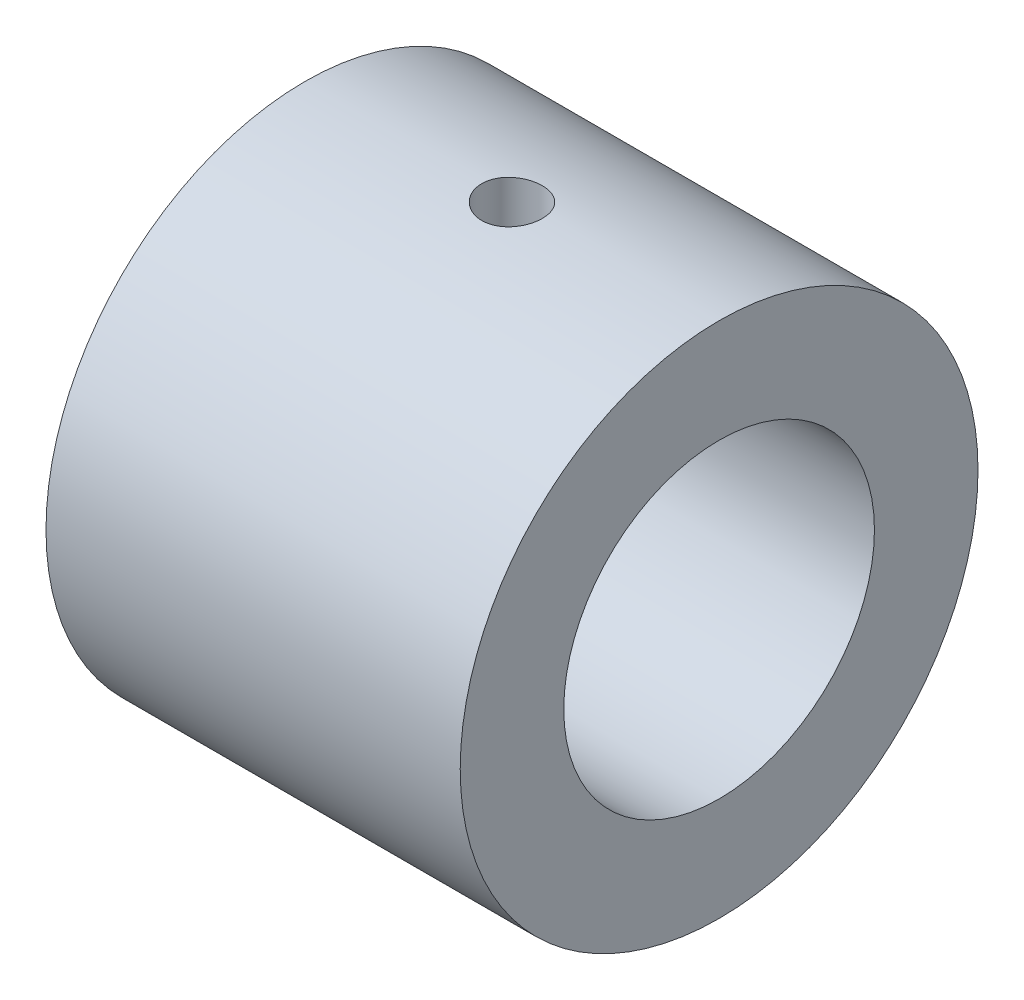
SolidWorks part; units mm, degrees
ref_plane "Front Plane" through (0, 0, 0) normal (0, 0, 1) x (1, 0, 0)
ref_plane "Top Plane" through (0, 0, 0) normal (0, 1, 0) x (1, 0, 0)
ref_plane "Right Plane" through (0, 0, 0) normal (1, 0, 0) x (0, 0, -1)
sketch "Sketch1" plane through (0, 0, 0) normal (1, 0, 0) x (0, 0, -1)
  circle A0 centre (0, 0) radius 15.875
  dimension "D1" = 31.75
extrude "Boss-Extrude1" add sketch "Sketch1" along normal mid plane 25.4
sketch "Sketch2" plane through (12.7, 0, 0) normal (1, 0, 0) x (0, 0, -1)
  circle A0 centre (0, 0) radius 9.525
  dimension "D1" = 19.05
extrude "3/4 Ream" cut sketch "Sketch2" against normal through all
sketch "Sketch3" plane through (0, 0, 0) normal (0, 1, 0) x (1, 0, 0)
  circle A0 centre (0, 0) radius 1.8542
  dimension "D1" = 3.7084
extrude "#10-32 Tap" cut sketch "Sketch3" along normal through all
